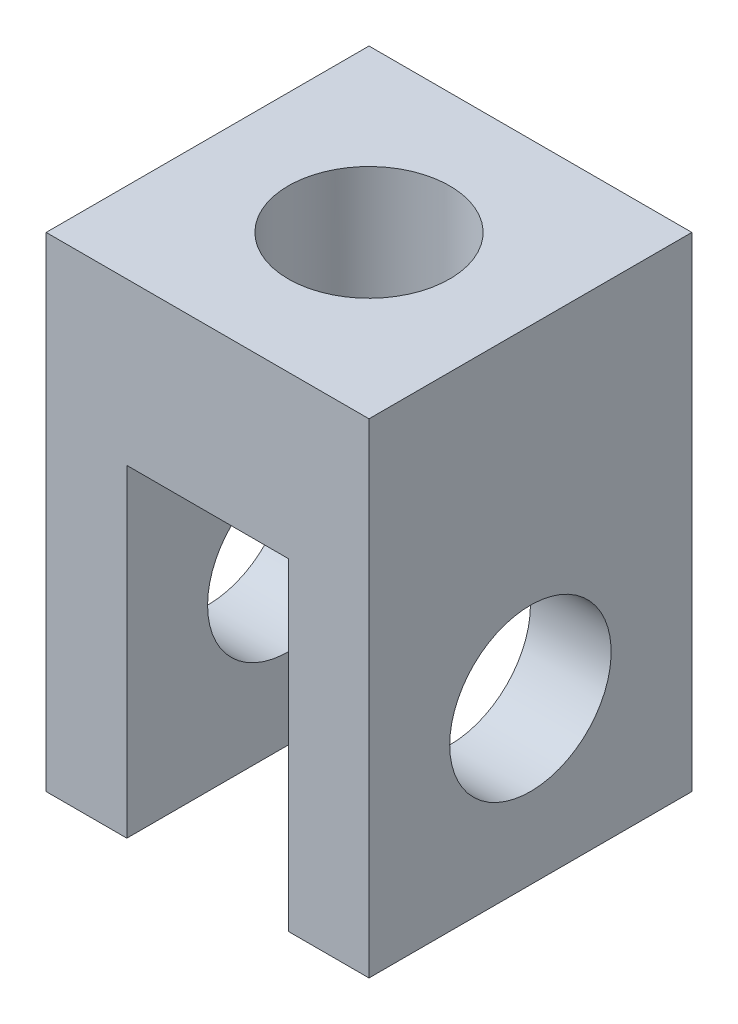
SolidWorks part; units mm, degrees
ref_plane "前视基准面" through (0, 0, 0) normal (0, 0, 1) x (1, 0, 0)
ref_plane "上视基准面" through (0, 0, 0) normal (0, 1, 0) x (1, 0, 0)
ref_plane "右视基准面" through (0, 0, 0) normal (1, 0, 0) x (0, 0, -1)
sketch "草图1" plane through (0, 0, 0) normal (0, 1, 0) x (1, 0, 0)
  line L1 (-10, 10) -> (10, 10)
  line L2 (-10, 10) -> (-10, -10)
  line L3 (-10, -10) -> (10, -10)
  line L4 (10, 10) -> (10, -10)
  line L5 (-10, 10) -> (10, -10) construction
  line L6 (-10, -10) -> (10, 10) construction
  point P0 (0, 0)
extrude "凸台-拉伸1" add sketch "草图1" along normal blind 10
sketch "草图2" plane through (0, 10, 0) normal (0, 1, 0) x (1, 0, 0)
  circle A0 centre (0, 0) radius 5
extrude "切除-拉伸2" cut sketch "草图2" against normal through all
sketch "草图3" plane through (0, 0, 0) normal (0, -1, 0) x (1, 0, 0)
  line L0 (-10, -10) -> (-10, 10) construction
  line L1 (-10, 10) -> (-5, 10)
  line L2 (-10, 10) -> (-10, -10)
  line L3 (-10, -10) -> (-5, -10)
  line L4 (-5, 10) -> (-5, -10)
  line L6 (10, 10) -> (5, 10)
  line L7 (10, 10) -> (10, -10)
  line L8 (10, -10) -> (5, -10)
  line L9 (5, 10) -> (5, -10)
extrude "凸台-拉伸2" add sketch "草图3" along normal blind 20
sketch "草图4" plane through (-10, 0, 0) normal (-1, 0, 0) x (0, 0, 1)
  circle A0 centre (0, -10) radius 5
extrude "切除-拉伸3" cut sketch "草图4" against normal through all
